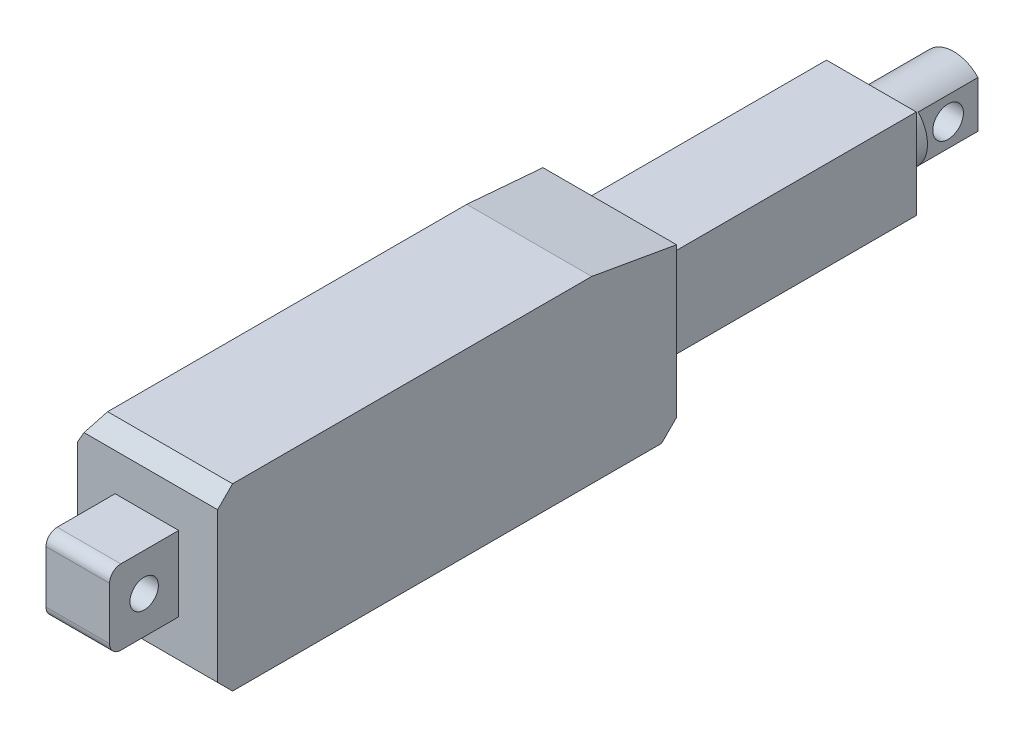
SolidWorks part; units mm, degrees
ref_plane "Front Plane" through (0, 0, 0) normal (0, 0, 1) x (1, 0, 0)
ref_plane "Top Plane" through (0, 0, 0) normal (0, 1, 0) x (1, 0, 0)
ref_plane "Right Plane" through (0, 0, 0) normal (1, 0, 0) x (0, 0, -1)
sketch "Sketch1" plane through (0, 0, 0) normal (0, 0, 1) x (1, 0, 0)
  line L1 (9.35, -12) -> (-9.35, -12)
  line L2 (9.35, -12) -> (9.35, 12)
  line L3 (9.35, 12) -> (-9.35, 12)
  line L4 (-9.35, -12) -> (-9.35, 12)
  line L5 (9.35, -12) -> (-9.35, 12) construction
  line L6 (9.35, 12) -> (-9.35, -12) construction
  point P0 (0, 0)
  dimension "D1" = 24
  dimension "D2" = 18.7
extrude "Boss-Extrude1" add sketch "Sketch1" along normal blind 61.35
chamfer "Chamfer1" distance 2 angle 60 2 edges at (-9.35, 12, 30.675) (-9.35, -12, 30.675)
chamfer "Chamfer2" distance 2 angle 45 3 edges at (1, 12, 61.35) (1, -12, 61.35) (1, -12, 0)
chamfer "Chamfer3" distance 2 angle 80 1 edges at (1, 12, 0)
sketch "Sketch2" plane through (0, 0, 0) normal (0, 0, -1) x (-1, 0, 0)
  line L1 (6, -6) -> (-6, -6)
  line L2 (6, -6) -> (6, 6)
  line L3 (6, 6) -> (-6, 6)
  line L4 (-6, -6) -> (-6, 6)
  line L5 (6, -6) -> (-6, 6) construction
  line L6 (6, 6) -> (-6, -6) construction
  point P0 (0, 0)
  dimension "D1" = 12
  dimension "D2" = 12
extrude "Boss-Extrude2" add sketch "Sketch2" along normal blind 35.4
sketch "Sketch3" plane through (0, 0, -35.4) normal (0, 0, -1) x (-1, 0, 0)
  circle A0 centre (0, 0) radius 4.5
  dimension "D1" = 9
extrude "Boss-Extrude3" add sketch "Sketch3" along normal blind 11
sketch "Sketch4" plane through (0, 0, -46.4) normal (0, 0, -1) x (-1, 0, 0)
  line L1 (3.25, -4.7401) -> (-3.25, -4.7401)
  line L2 (3.25, -4.7401) -> (3.25, 4.7401)
  line L3 (3.25, 4.7401) -> (-3.25, 4.7401)
  line L4 (-3.25, -4.7401) -> (-3.25, 4.7401)
  line L5 (3.25, -4.7401) -> (-3.25, 4.7401) construction
  line L6 (3.25, 4.7401) -> (-3.25, -4.7401) construction
  line L7 (5.5933, -4.7401) -> (-5.5933, -4.7401)
  line L8 (5.5933, -4.7401) -> (5.5933, 4.7401)
  line L9 (5.5933, 4.7401) -> (-5.5933, 4.7401)
  line L10 (-5.5933, -4.7401) -> (-5.5933, 4.7401)
  line L11 (5.5933, -4.7401) -> (-5.5933, 4.7401) construction
  line L12 (5.5933, 4.7401) -> (-5.5933, -4.7401) construction
  point P0 (0, 0)
  point P6 (0, 0)
  circle M5 centre (0, 0) radius 4.5
  dimension "D1" = 6.5
extrude "Cut-Extrude1" cut sketch "Sketch4" against normal blind 8 contours L4 M5 | L2 M5
sketch "Sketch5" plane through (0, 0, 61.35) normal (0, 0, 1) x (1, 0, 0)
  line L0 (9.35, -10) -> (9.35, 10) construction
  line L1 (-4.35, -5) -> (4.15, -5)
  line L2 (-4.35, -5) -> (-4.35, 5)
  line L3 (-4.35, 5) -> (4.15, 5)
  line L4 (4.15, -5) -> (4.15, 5)
  line L5 (-4.35, -5) -> (4.15, 5) construction
  line L6 (-4.35, 5) -> (4.15, -5) construction
  point P0 (0, 0)
  dimension "D1" = 8.5
  dimension "D2" = 10
  dimension "D3" = 5.2
  dimension "D4" = 5
extrude "Boss-Extrude4" add sketch "Sketch5" along normal blind 9.24
sketch "Sketch7" plane through (4.15, 0, 0) normal (1, 0, 0) x (0, 0, -1)
  circle A0 centre (-65.97, 0) radius 1.9
  dimension "D1" = 3.8
extrude "Cut-Extrude2" cut sketch "Sketch7" against normal blind 10
fillet "Fillet1" radius 1.5 2 edges at (-0.1, -5, 70.59) (-0.1, 5, 70.59)
sketch "Sketch8" plane through (3.25, 0, 0) normal (1, 0, 0) x (0, 0, -1)
  circle A0 centre (42.4, 0) radius 2.05
  dimension "D1" = 4.1
extrude "Cut-Extrude3" cut sketch "Sketch8" against normal through all
